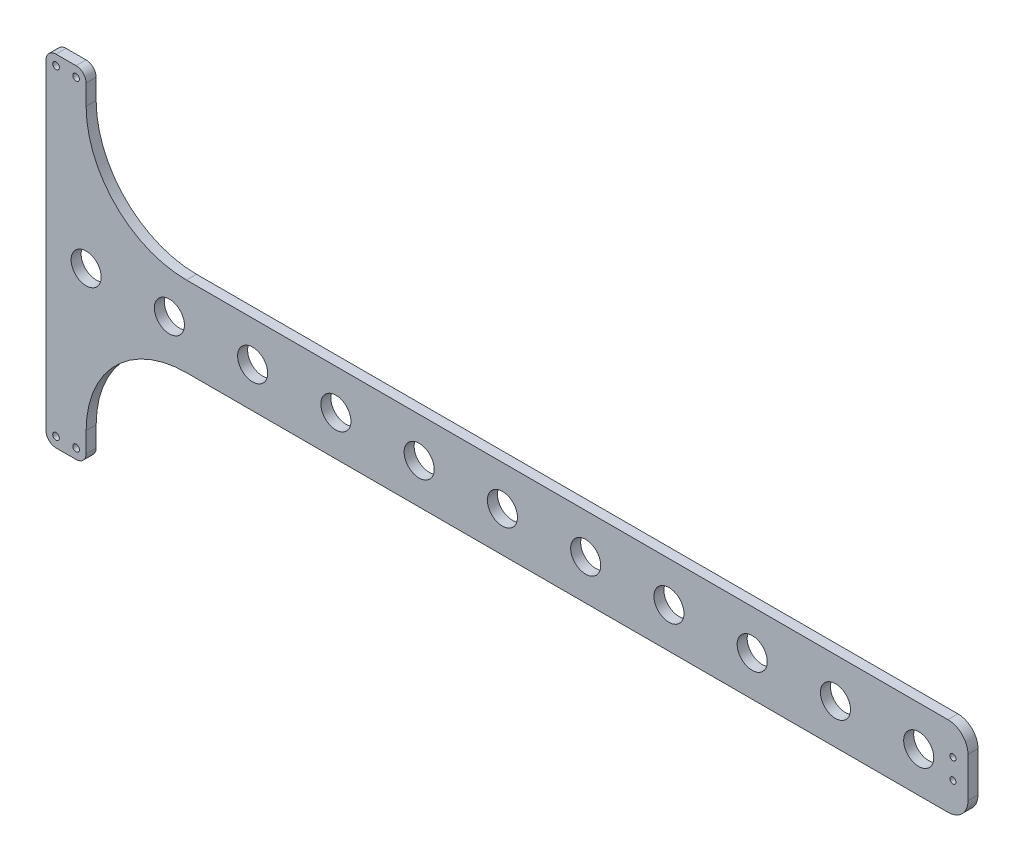
SolidWorks part; units mm, degrees
material "ﾎﾟﾘｴﾁﾚﾝｲﾐﾝ(PEI)"
ref_plane "正面" through (0, 0, 0) normal (0, 0, 1) x (1, 0, 0)
ref_plane "平面" through (0, 0, 0) normal (0, 1, 0) x (1, 0, 0)
ref_plane "右側面" through (0, 0, 0) normal (1, 0, 0) x (0, 0, -1)
sketch "ｽｹｯﾁ1" plane through (0, 0, 0) normal (0, 0, 1) x (1, 0, 0)
  line L0 (0, -80) -> (0, 80) construction
  line L1 (0, 0) -> (454.55, 0) construction
  line L2 (0, 80) -> (10, 80) construction
  line L3 (0, -80) -> (10, -80) construction
  line L4 (454.55, 20) -> (15, 20)
  line L5 (-5, 85) -> (15, 85)
  line L6 (-5, 85) -> (-5, -85)
  line L7 (-5, -85) -> (15, -85)
  line L8 (15, 85) -> (15, -85)
  line L9 (454.55, 0) -> (15, 0)
  line L10 (454.55, 20) -> (454.55, -20)
  line L11 (454.55, -20) -> (15, -20)
  line L12 (15, 20) -> (15, -20)
  circle A0 centre (0, 80) radius 1.65
  circle A1 centre (10, 80) radius 1.65
  circle A2 centre (10, -80) radius 1.65
  circle A3 centre (0, -80) radius 1.65
  dimension "D2" = 3.3
  dimension "D4" = 3.3
  dimension "D6" = 5
  dimension "D1" = 160
  dimension "D3" = 10
  dimension "D5" = 5
  dimension "D7" = 5
  dimension "D8" = 5
  dimension "D9" = 454.55
  dimension "D10" = 20
extrude "ﾎﾞｽ - 押し出し1" add sketch "ｽｹｯﾁ1" along normal blind 5 contours L10 L4 L8 L9 | L11 L10 L9 L8 | L8 L5 L6 L7 A2 A1 A0 A3
fillet "ﾌｨﾚｯﾄ1" radius 50 2 edges at (15, -20, 2.5) (15, 20, 2.5)
fillet "ﾌｨﾚｯﾄ2" radius 5 4 edges at (-5, -85, 2.5) (15, -85, 2.5) (-5, 85, 2.5) (15, 85, 2.5)
sketch "ｽｹｯﾁ2" plane through (0, 0, 5) normal (0, 0, 1) x (1, 0, 0)
  line L0 (-5, 0) -> (454.55, 0) construction
  line L1 (-5, 80) -> (-5, -80) construction
  line L2 (454.55, 20) -> (454.55, -20) construction
  line L3 (447.05, 0) -> (447.05, 5) construction
  circle A2 centre (447.05, 5) radius 1.5
  circle A3 centre (447.05, -5) radius 1.5
  dimension "D1" = 5
  dimension "D2" = 3
  dimension "D3" = 7.5
extrude "ｶｯﾄ - 押し出し1" cut sketch "ｽｹｯﾁ2" against normal blind 10
fillet "ﾌｨﾚｯﾄ3" radius 10 2 edges at (454.55, -20, 2.5) (454.55, 20, 2.5)
sketch "ｽｹｯﾁ3" plane through (0, 0, 5) normal (0, 0, 1) x (1, 0, 0)
  line L0 (-5, 0) -> (454.55, 0) construction
  line L1 (-5, 80) -> (-5, -80) construction
  line L2 (454.55, 10) -> (454.55, -10) construction
  circle A0 centre (15, 0) radius 7.5
  circle A1 centre (56.5, 0) radius 7.5
  circle A2 centre (98, 0) radius 7.5
  circle A3 centre (139.5, 0) radius 7.5
  circle A4 centre (181, 0) radius 7.5
  circle A5 centre (222.5, 0) radius 7.5
  circle A6 centre (264, 0) radius 7.5
  circle A7 centre (305.5, 0) radius 7.5
  circle A8 centre (347, 0) radius 7.5
  circle A9 centre (388.5, 0) radius 7.5
  circle A10 centre (430, 0) radius 7.5
  point P9 (427.7714, 0)
  dimension "D1" = 15
  dimension "D2" = 20
  dimension "D4" = 41.5
  dimension "D3" = 11
extrude "ｶｯﾄ - 押し出し2" cut sketch "ｽｹｯﾁ3" against normal blind 10
